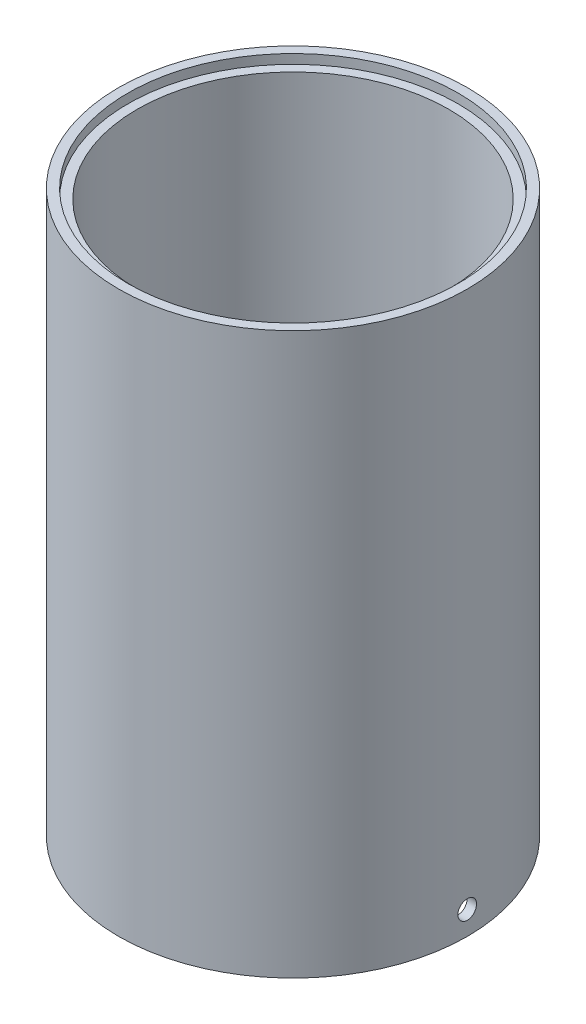
SolidWorks part; units mm, degrees
ref_plane "Front Plane" through (0, 0, 0) normal (0, 0, 1) x (1, 0, 0)
ref_plane "Top Plane" through (0, 0, 0) normal (0, 1, 0) x (1, 0, 0)
ref_plane "Right Plane" through (0, 0, 0) normal (1, 0, 0) x (0, 0, -1)
sketch "Sketch1" plane through (0, 0, 0) normal (0, 1, 0) x (1, 0, 0)
  circle A0 centre (0, 0) radius 50
  dimension "D1" = 100
extrude "Extrude-Thin1" add sketch "Sketch1" along normal blind 180 thin contours A0
sketch "Sketch2" plane through (0, 180, 0) normal (0, 1, 0) x (1, 0, 0)
  circle A0 centre (0, 0) radius 53
  dimension "D1" = 106
extrude "Cut-Extrude1" cut sketch "Sketch2" against normal blind 3
sketch "Sketch3" plane through (0, 0, 0) normal (0, -1, 0) x (1, 0, 0)
  circle A0 centre (0, 0) radius 53
  dimension "D1" = 106
extrude "Cut-Extrude2" cut sketch "Sketch3" against normal blind 15
ref_plane "Plane1" through (53, 0, 0) normal (-1, 0, 0) x (0, 0, 1)
sketch "Sketch5" plane through (53, 0, 0) normal (-1, 0, 0) x (0, 0, 1)
  line L0 (0, 15) -> (0, 0) construction
  line L1 (-50, 15) -> (50, 15) construction
  circle A0 centre (0, 7.5) radius 3
  point P7 (8.7807, 9.8904)
  point P8 (0, 7.5)
  dimension "D1" = 6
extrude "Cut-Extrude3" cut sketch "Sketch5" along normal through all both and the other way through all
